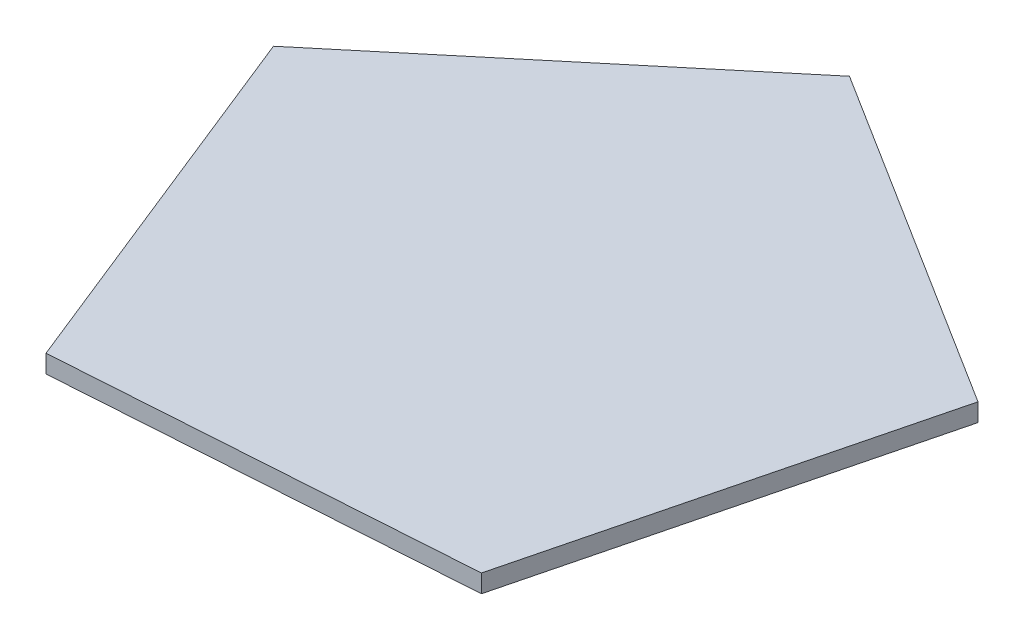
SolidWorks part; units mm, degrees
ref_plane "Front Plane" through (0, 0, 0) normal (0, 0, 1) x (1, 0, 0)
ref_plane "Top Plane" through (0, 0, 0) normal (0, 1, 0) x (1, 0, 0)
ref_plane "Right Plane" through (0, 0, 0) normal (1, 0, 0) x (0, 0, -1)
sketch "Sketch1" plane through (0, 0, 0) normal (0, 1, 0) x (1, 0, 0)
  line L1 (-59.9258, 15.1181) -> (-32.8962, -52.3211)
  line L2 (-32.8962, -52.3211) -> (39.5948, -47.4543)
  line L3 (39.5948, -47.4543) -> (57.3672, 22.9927)
  line L4 (57.3672, 22.9927) -> (-4.14, 61.6646)
  line L5 (-4.14, 61.6646) -> (-59.9258, 15.1181)
  circle A0 centre (0, 0) radius 50 construction
  dimension "D1" = 100
extrude "Boss-Extrude1" add sketch "Sketch1" along normal blind 3.2
